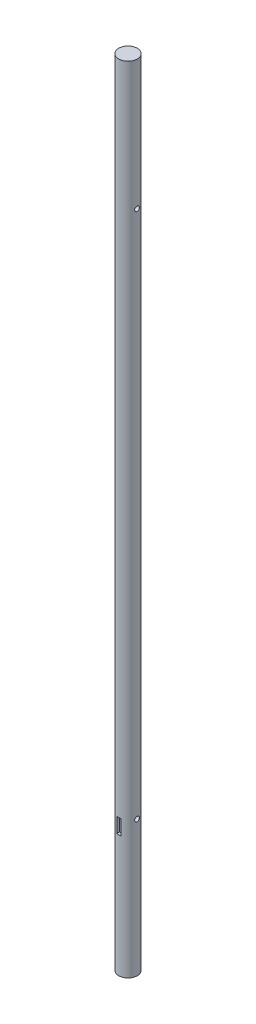
SolidWorks part; units mm, degrees
material "7075-T6 (SN)"
ref_plane "Alzado" through (0, 0, 0) normal (0, 0, 1) x (1, 0, 0)
ref_plane "Planta" through (0, 0, 0) normal (0, 1, 0) x (1, 0, 0)
ref_plane "Vista lateral" through (0, 0, 0) normal (1, 0, 0) x (0, 0, -1)
sketch "Croquis1" plane through (0, 0, 0) normal (0, 1, 0) x (1, 0, 0)
  circle A0 centre (0, 0) radius 18.75
  dimension "D1" = 37.5
extrude "Saliente-Extruir1" add sketch "Croquis1" along normal blind 1600
sketch "Croquis2" plane through (0, 0, 0) normal (0, 0, 1) x (1, 0, 0)
  line L0 (0, 1600) -> (0, 0) construction
  line L1 (18.75, 1600) -> (-18.75, 1600) construction
ref_plane "Plano1" through (0, 0, 18.75) normal (0, 0, 1) x (1, 0, 0)
sketch "Croquis3" plane through (0, 0, 18.75) normal (0, 0, 1) x (1, 0, 0)
  line L0 (0, 800) -> (0, 300) construction
  line L1 (0, 1600) -> (0, 0) construction
  line L2 (0, 300) -> (0, 280) construction
  line L4 (4.075, 246.0622) -> (-4.075, 246.0622)
  line L5 (4.075, 246.0622) -> (4.075, 276.0622)
  line L6 (4.075, 276.0622) -> (-4.075, 276.0622)
  line L7 (-4.075, 246.0622) -> (-4.075, 276.0622)
  line L8 (4.075, 246.0622) -> (-4.075, 276.0622) construction
  line L9 (4.075, 276.0622) -> (-4.075, 246.0622) construction
  point P4 (0, 261.0622)
  dimension "D1" = 500
  dimension "D2" = 20
  dimension "D3" = 8.15
  dimension "D4" = 30
extrude "Cortar-Extruir1" cut sketch "Croquis3" against normal blind 5.75
mirror "Simetría1" about plane through (0, 0, 0) normal (0, 0, 1) of "Cortar-Extruir1"
sketch "Croquis5" plane through (0, 0, 0) normal (1, 0, 0) x (0, 0, -1)
  line L0 (0, 1600) -> (0, 800) construction
  line L1 (18.75, 1600) -> (-18.75, 1600) construction
  line L2 (0, 800) -> (0, 290) construction
  line L3 (0, 290) -> (0, 273.56) construction
  circle A0 centre (0, 273.56) radius 4.7625
  dimension "D4" = 9.525
  dimension "D1" = 800
  dimension "D2" = 510
  dimension "D3" = 16.44
ref_plane "Plano3" through (0, 800, 0) normal (0, 1, 0) x (1, 0, 0)
extrude "Cortar-Extruir2" cut sketch "Croquis5" against normal through all and the other way through all
sketch "Croquis6" plane through (0, 0, 0) normal (1, 0, 0) x (0, 0, -1)
  line L0 (0, 1600) -> (0, 1338.56) construction
  line L1 (18.75, 1600) -> (-18.75, 1600) construction
  circle A0 centre (0, 1338.56) radius 4.7625
  dimension "D2" = 9.525
  dimension "D1" = 261.44
extrude "Cortar-Extruir3" cut sketch "Croquis6" against normal through all and the other way through all
